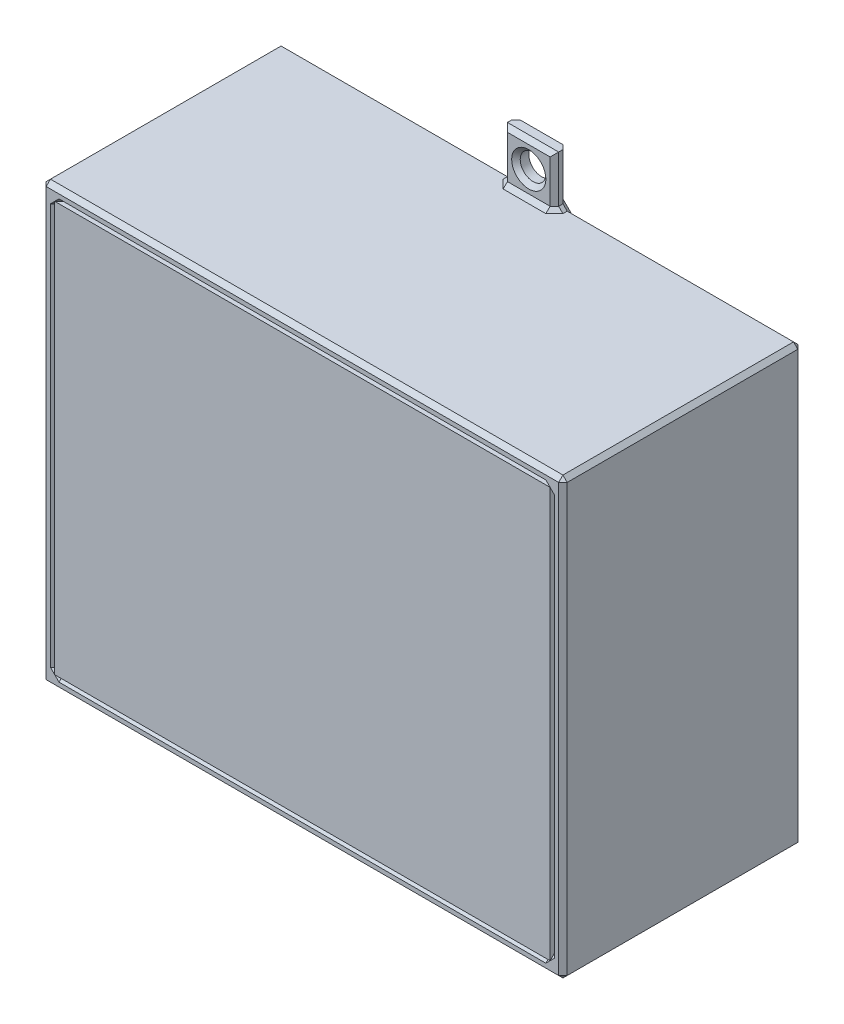
SolidWorks part; units mm, degrees
ref_plane "前视基准面" through (0, 0, 0) normal (0, 0, 1) x (1, 0, 0)
ref_plane "上视基准面" through (0, 0, 0) normal (0, 1, 0) x (1, 0, 0)
ref_plane "右视基准面" through (0, 0, 0) normal (1, 0, 0) x (0, 0, -1)
other "Configuration Table"
sketch "草图1" plane through (0, 0, 0) normal (0, 0, 1) x (1, 0, 0)
  line L8 (-8, 8) -> (-8, -88)
  line L9 (-8, -88) -> (108, -88)
  line L10 (108, -88) -> (108, 8)
  line L11 (108, 8) -> (-8, 8)
  line L12 (-8, 8) -> (-8, -88)
  line L13 (-8, -88) -> (108, -88)
  line L14 (108, -88) -> (108, 8)
  line L15 (108, 8) -> (-8, 8)
  dimension "D1" = 8
extrude "凸台-拉伸1" add sketch "草图1" along normal blind 3
sketch "草图2" plane through (0, 0, 0) normal (0, 0, -1) x (-1, 0, 0)
  line L8 (11, 11) -> (-111, 11)
  line L9 (-111, 11) -> (-111, -91)
  line L10 (-111, -91) -> (11, -91)
  line L11 (11, -91) -> (11, 11)
  line L12 (11, 11) -> (-111, 11)
  line L13 (-111, 11) -> (-111, -91)
  line L14 (-111, -91) -> (11, -91)
  line L15 (11, -91) -> (11, 11)
  line L20 (8, 8) -> (-108, 8)
  line L21 (-108, 8) -> (-108, -88)
  line L22 (-108, -88) -> (8, -88)
  line L23 (8, -88) -> (8, 8)
  line L24 (8, 8) -> (-108, 8)
  line L25 (-108, 8) -> (-108, -88)
  line L26 (-108, -88) -> (8, -88)
  line L27 (8, -88) -> (8, 8)
  dimension "D1" = 3
  dimension "D2" = 0
extrude "凸台-拉伸2" add sketch "草图2" along normal offset from surface 8 and the other way up to surface separate body
sketch "草图3" plane through (0, -91, 0) normal (0, -1, 0) x (1, 0, 0)
  line L1 (35, -15) -> (65, -15)
  line L2 (35, -15) -> (35, 0)
  line L3 (35, 0) -> (65, 0)
  line L4 (65, -15) -> (65, 0)
  line L6 (50, 3) -> (50, -15) construction
  line L7 (111, 3) -> (-11, 3) construction
  line L8 (-8, 0) -> (108, 0) construction
  point P4 (0, 0)
  point P5 (0, 0)
  point P6 (0, 0)
  dimension "D1" = 15
  dimension "D2" = 30
extrude "切除-拉伸1" cut sketch "草图3" against normal blind 8
sketch "草图4" plane through (-11, 0, 0) normal (-1, 0, 0) x (0, 0, 1)
  line L0 (0, 0) -> (0, -80) construction
  line L1 (0, -25) -> (-15, -25)
  line L2 (0, -25) -> (0, -55)
  line L3 (0, -55) -> (-15, -55)
  line L4 (-15, -25) -> (-15, -55)
  line L5 (3, -40) -> (-53, -40) construction
  line L6 (3, -91) -> (3, 11) construction
  line L7 (-53, 11) -> (-53, -91) construction
  dimension "D1" = 30
  dimension "D2" = 15
sketch "草图5" plane through (0, 0, -53) normal (0, 0, -1) x (-1, 0, 0)
  line L0 (-111, 11) -> (11, 11) construction
  line L1 (-44, 11) -> (-56, 11)
  line L2 (-44, 11) -> (-44, 23)
  line L3 (-44, 23) -> (-56, 23)
  line L4 (-56, 11) -> (-56, 23)
  line L5 (-50, 8) -> (-50, 0) construction
  line L6 (-108, 8) -> (8, 8) construction
  line L7 (-100, 0) -> (0, 0) construction
  circle A0 centre (-50, 17) radius 3
  dimension "D3" = 6
  dimension "D4" = 6
  dimension "D1" = 12
  dimension "D2" = 12
  dimension "D5" = 6
extrude "切除-拉伸2" cut sketch "草图4" against normal blind 3
extrude "凸台-拉伸6" add sketch "草图5" against normal blind 3
chamfer "倒角3" distance 1 angle 45 50 edges at (-8, -55, -7.5) (-8, -40, -15) (-8, -25, -7.5) (-8, -40, 0) (50, -88, 0) (65, -88, -7.5) (50, -88, -15) (35, -88, -7.5) (-8, -40, 3) (-8, -40, -53) (-8, 8, -25) (50, 8, 3) (50, 8, -53) (50, -88, 3) (-8, -88, -25) (50, -88, -53) (108, 8, -25) (108, -40, 3) (108, -88, -25) (108, -40, -53) (-11, -40, -15) (-11, -55, -7.5) (-11, -40, 0) (-11, -25, -7.5) (65, -91, -7.5) (50, -91, 0) (35, -91, -7.5) (50, -91, -15) (47, 17, -50) (56, 17, -53) (44, 17, -53) (-11, -40, 3) (-11, -40, -53) (50, -91, 3) (-11, -91, -25) (50, -91, -53) (111, -40, 3) (111, -91, -25) (111, -40, -53) (50, 23, -50) (56, 17, -50) (44, 17, -50) (83.5, 11, -53) (111, 11, -25) (50, 11, 3) (-11, 11, -25) (16.5, 11, -53) (44, 11, -51.5) (50, 11, -50) (56, 11, -51.5)
